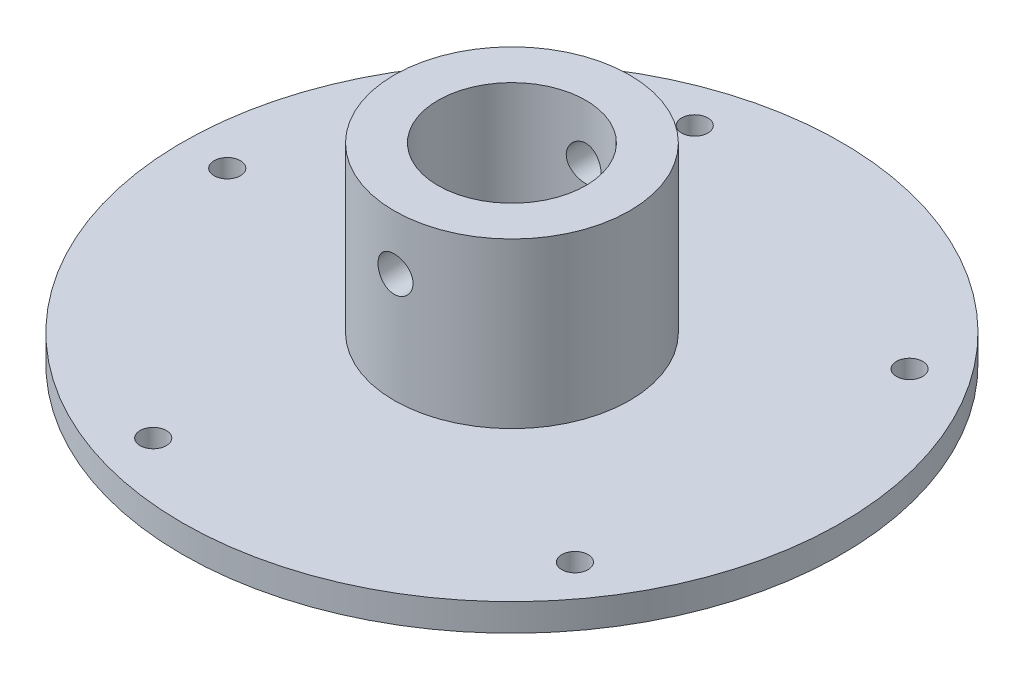
SolidWorks part; units mm, degrees
ref_plane "Front Plane" through (0, 0, 0) normal (0, 0, 1) x (1, 0, 0)
ref_plane "Top Plane" through (0, 0, 0) normal (0, 1, 0) x (1, 0, 0)
ref_plane "Right Plane" through (0, 0, 0) normal (1, 0, 0) x (0, 0, -1)
sketch "Sketch1" plane through (0, 0, 0) normal (0, 1, 0) x (1, 0, 0)
  circle A0 centre (0, 0) radius 30.1
  circle A1 centre (-26, 0) radius 1.2
  circle A2 centre (-8.0344, 24.7275) radius 1.2
  circle A3 centre (21.0344, 15.2824) radius 1.2
  circle A4 centre (21.0344, -15.2824) radius 1.2
  circle A5 centre (-8.0344, -24.7275) radius 1.2
  circle A6 centre (0, 0) radius 6.75
  point P16 (0, 0)
  dimension "D1" = 60.2
  dimension "D3" = 2.4
  dimension "D5" = 13.5
  dimension "D2" = 26
  dimension "D4" = 5
extrude "Boss-Extrude1" add sketch "Sketch1" along normal blind 2.5
sketch "Sketch2" plane through (0, 2.5, 0) normal (0, 1, 0) x (1, 0, 0)
  circle A0 centre (0, 0) radius 6.75 construction
  circle A1 centre (0, 0) radius 6.75
  circle A2 centre (0, 0) radius 10.75
  dimension "D1" = 4
extrude "Boss-Extrude2" add sketch "Sketch2" along normal blind 15
sketch "Sketch3" plane through (0, 0, 0) normal (0, 0, 1) x (1, 0, 0)
  line L0 (0, 12.5) -> (0, 17.5) construction
  line L1 (10.75, 17.5) -> (-10.75, 17.5) construction
  circle A0 centre (0, 12.5) radius 1.6
  dimension "D1" = 3.2
  dimension "D2" = 5
extrude "Cut-Extrude1" cut sketch "Sketch3" against normal through all both and the other way through all
